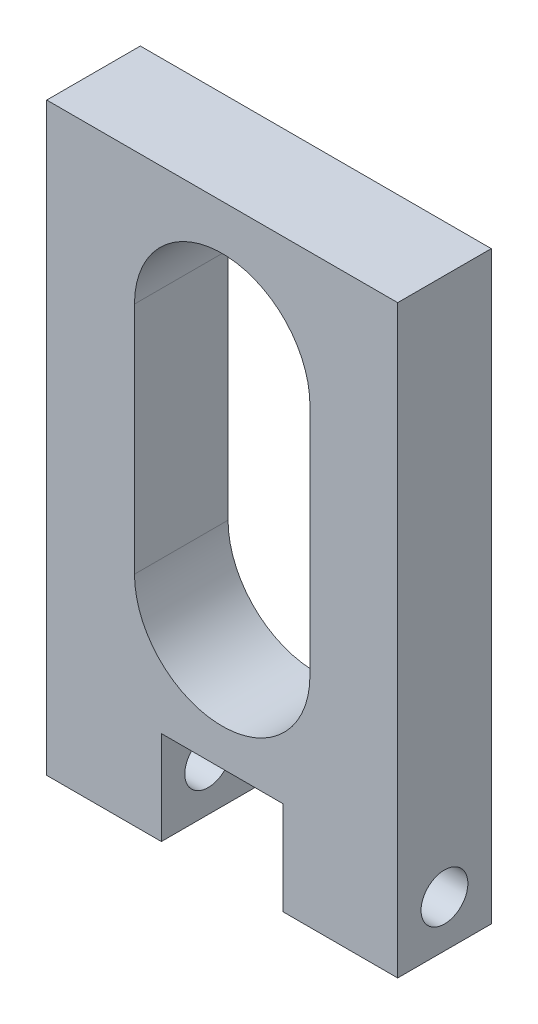
SolidWorks part; units mm, degrees
ref_plane "Front Plane" through (0, 0, 0) normal (0, 0, 1) x (1, 0, 0)
ref_plane "Top Plane" through (0, 0, 0) normal (0, 1, 0) x (1, 0, 0)
ref_plane "Right Plane" through (0, 0, 0) normal (1, 0, 0) x (0, 0, -1)
sketch "Sketch1" plane through (0, 0, 0) normal (0, 0, 1) x (1, 0, 0)
  line L0 (0, 0) -> (12.446, 0)
  line L2 (0, 0) -> (0, 63.5)
  line L3 (0, 63.5) -> (38.1, 63.5)
  line L4 (38.1, 0) -> (38.1, 63.5)
  line L5 (12.446, 0) -> (12.446, 10.16)
  line L6 (12.446, 10.16) -> (25.654, 10.16)
  line L7 (25.654, 10.16) -> (25.654, 0)
  line L8 (25.654, 0) -> (38.1, 0)
  line L9 (9.525, 49.0785) -> (9.525, 23.6785)
  line L10 (28.575, 49.0785) -> (28.575, 23.6785)
  arc A1 (9.525, 49.0785) -> (28.575, 49.0785) centre (19.05, 49.0785) cw
  arc A2 (9.525, 23.6785) -> (28.575, 23.6785) centre (19.05, 23.6785) ccw
  point P15 (0, 0)
  point P16 (19.05, 63.5)
  point P17 (19.05, 49.0785)
  dimension "D5" = 9.525
  dimension "D1" = 38.1
  dimension "D2" = 63.5
  dimension "D3" = 13.208
  dimension "D4" = 10.16
  dimension "D6" = 25.4
extrude "Boss-Extrude2" add sketch "Sketch1" along normal blind 10.16
sketch "Sketch4" plane through (0, 0, 0) normal (-1, 0, 0) x (0, 0, 1)
  line L0 (10.16, 0) -> (0, 0) construction
  line L1 (5.08, 5.08) -> (5.08, 0) construction
  circle A0 centre (5.08, 5.08) radius 2.54
  dimension "D1" = 5.08
  dimension "D2" = 5.08
extrude "Cut-Extrude1" cut sketch "Sketch4" against normal blind 38.1
